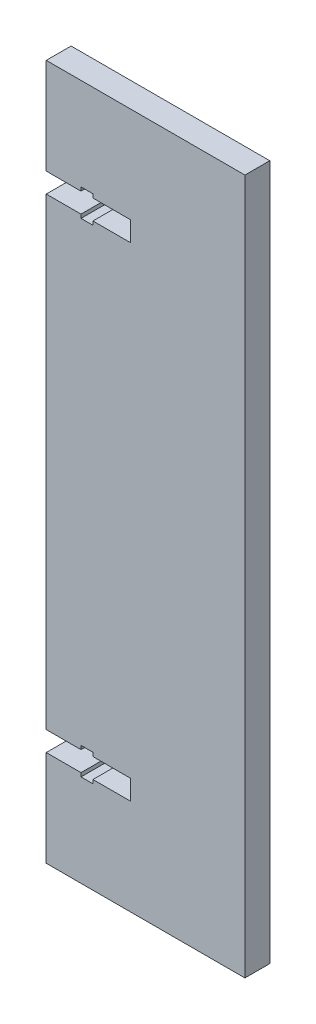
SolidWorks part; units mm, degrees
ref_plane "Front Plane" through (0, 0, 0) normal (0, 0, 1) x (1, 0, 0)
ref_plane "Top Plane" through (0, 0, 0) normal (0, 1, 0) x (1, 0, 0)
ref_plane "Right Plane" through (0, 0, 0) normal (1, 0, 0) x (0, 0, -1)
sketch "Sketch1" plane through (0, 0, 0) normal (0, 0, 1) x (1, 0, 0)
  line L1 (-35.2855, 88.5616) -> (4.7145, 88.5616)
  line L2 (-35.2855, 88.5616) -> (-35.2855, -51.4384)
  line L3 (-35.2855, -51.4384) -> (4.7145, -51.4384)
  line L4 (4.7145, 88.5616) -> (4.7145, -51.4384)
  line L13 (4.7145, 88.5616) -> (-11.2855, 88.5616) construction
  line L15 (4.7145, -51.4384) -> (-11.2855, -51.4384) construction
  dimension "D1" = 40
extrude "Boss-Extrude1" add sketch "Sketch1" along normal blind 5
sketch "Sketch4" plane through (0, 0, 0) normal (0, 0, -1) x (-1, 0, 0)
  line L9 (-4.7145, -51.4384) -> (-4.7145, 88.5616) construction
  line L10 (35.2855, -51.4384) -> (-4.7145, -51.4384) construction
  line L50 (15.2855, 88.5616) -> (15.2855, -51.4384) construction
  line L51 (-4.7145, 88.5616) -> (35.2855, 88.5616) construction
  line L52 (-4.7145, 18.5616) -> (35.2855, 18.5616) construction
  line L53 (35.2855, 88.5616) -> (35.2855, -51.4384) construction
  line L66 (35.2855, 65.2517) -> (28.2855, 65.2517)
  line L67 (18.2855, 65.2517) -> (18.2855, 69.2517)
  line L68 (18.2855, 69.2517) -> (25.8855, 69.2517)
  line L69 (28.2855, 65.2517) -> (28.2855, 64.5017)
  line L70 (28.2855, 64.5017) -> (25.8855, 64.5017)
  line L71 (25.8855, 64.5017) -> (25.8855, 65.2517)
  line L72 (25.8855, 69.2517) -> (25.8855, 70.0017)
  line L73 (25.8855, 70.0017) -> (28.2855, 70.0017)
  line L74 (28.2855, 70.0017) -> (28.2855, 69.2517)
  line L75 (25.8855, 65.2517) -> (18.2855, 65.2517)
  line L76 (28.2855, 69.2517) -> (35.2855, 69.2517)
  line L77 (35.2855, 65.2517) -> (35.2855, 69.2517)
  line L78 (35.2855, -28.1285) -> (35.2855, -32.1285)
  line L79 (28.2855, -32.1285) -> (35.2855, -32.1285)
  line L80 (25.8855, -28.1285) -> (18.2855, -28.1285)
  line L81 (28.2855, -32.8785) -> (28.2855, -32.1285)
  line L82 (25.8855, -32.8785) -> (28.2855, -32.8785)
  line L83 (25.8855, -32.1285) -> (25.8855, -32.8785)
  line L84 (25.8855, -27.3785) -> (25.8855, -28.1285)
  line L85 (28.2855, -27.3785) -> (25.8855, -27.3785)
  line L86 (28.2855, -28.1285) -> (28.2855, -27.3785)
  line L87 (18.2855, -32.1285) -> (25.8855, -32.1285)
  line L88 (18.2855, -28.1285) -> (18.2855, -32.1285)
  line L89 (35.2855, -28.1285) -> (28.2855, -28.1285)
extrude "Cut-Extrude1" cut sketch "Sketch4" against normal blind 10
